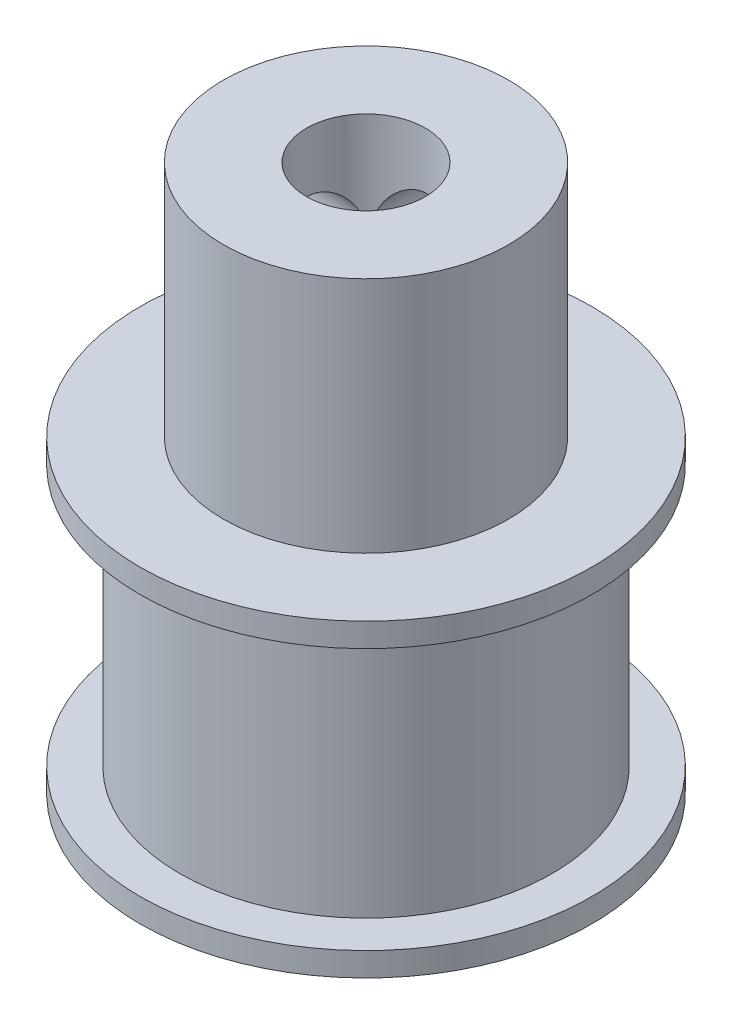
SolidWorks part; units mm, degrees
ref_plane "前视基准面" through (0, 0, 0) normal (0, 0, 1) x (1, 0, 0)
ref_plane "上视基准面" through (0, 0, 0) normal (0, 1, 0) x (1, 0, 0)
ref_plane "右视基准面" through (0, 0, 0) normal (1, 0, 0) x (0, 0, -1)
sketch "草图1" plane through (0, 0, 0) normal (0, 1, 0) x (1, 0, 0)
  circle A0 centre (0, 0) radius 9.5
  dimension "D1" = 19
extrude "凸台-拉伸1" add sketch "草图1" along normal blind 1
sketch "草图2" plane through (0, 1, 0) normal (0, 1, 0) x (1, 0, 0)
  circle A0 centre (0, 0) radius 7.83
  dimension "D1" = 15.66
extrude "凸台-拉伸2" add sketch "草图2" along normal blind 11
sketch "草图3" plane through (0, 12, 0) normal (0, 1, 0) x (1, 0, 0)
  circle A0 centre (0, 0) radius 9.5
  dimension "D1" = 19
extrude "凸台-拉伸3" add sketch "草图3" along normal blind 1
sketch "草图4" plane through (0, 13, 0) normal (0, 1, 0) x (1, 0, 0)
  circle A0 centre (0, 0) radius 6
  dimension "D1" = 12
extrude "凸台-拉伸4" add sketch "草图4" along normal blind 10
sketch "草图5" plane through (0, 23, 0) normal (0, 1, 0) x (1, 0, 0)
  circle A0 centre (0, 0) radius 2.5
  dimension "D1" = 5
extrude "切除-拉伸1" cut sketch "草图5" against normal through all
hole_wizard "M4 螺纹孔1" positions "3D草图1" profile "草图6" tap size "M4" standard "GB"
sketch3d "3D草图1"
  point P0 (-5.9927, 18.8335, -0.2951)
sketch "草图6" plane through (-5.9927, 18.8335, -0.2951) normal (0, 1, 0) x (-0.0492, 0, 0.9988)
  line L0 (0, 0) -> (0, 3.5)
  line L1 (0, 3.5) -> (1.65, 3.5)
  line L2 (1.65, 3.5) -> (1.65, 0)
  line L5 (1.65, 0) -> (0, 0)
  line L11 (0, -6.35) -> (0, 107.95) construction
  dimension "通孔螺纹孔钻头直径" = 3.3
  dimension "通孔螺纹孔钻头深度" = 3.5
cosmetic thread "孔螺蚊线1" parameters "D2"=4
hole_wizard "M4 螺纹孔2" positions "3D草图2" profile "草图7" tap size "M4" standard "GB"
sketch3d "3D草图2"
  point P0 (0.1682, 18.9888, -5.9976)
sketch "草图7" plane through (0.1682, 18.9888, -5.9976) normal (0, 1, 0) x (-0.9996, 0, -0.028)
  line L0 (0, 0) -> (0, 3.5)
  line L1 (0, 3.5) -> (1.65, 3.5)
  line L2 (1.65, 3.5) -> (1.65, 0)
  line L5 (1.65, 0) -> (0, 0)
  line L11 (0, -6.35) -> (0, 107.95) construction
  dimension "通孔螺纹孔钻头直径" = 3.3
  dimension "通孔螺纹孔钻头深度" = 3.5
cosmetic thread "孔螺蚊线2" parameters "D2"=4
